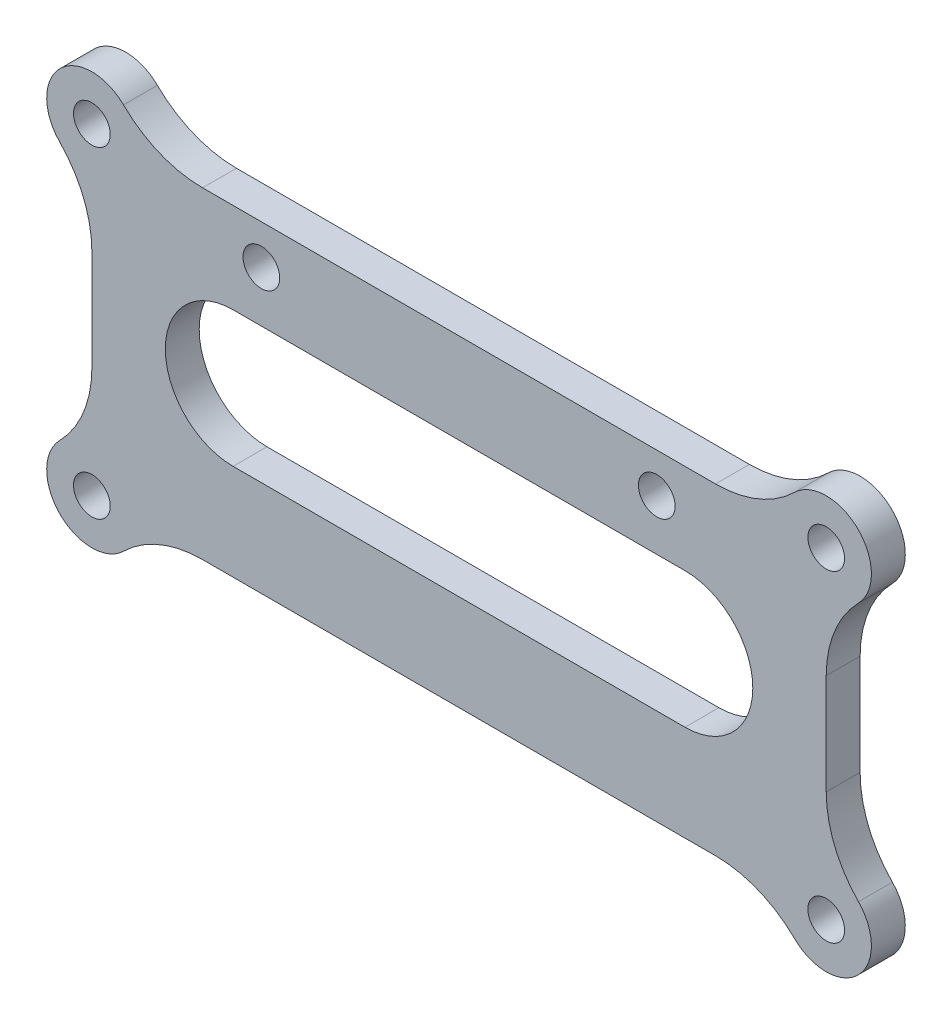
SolidWorks part; units mm, degrees
material "ABS"
ref_plane "Спереди" through (0, 0, 0) normal (0, 0, 1) x (1, 0, 0)
ref_plane "Сверху" through (0, 0, 0) normal (0, 1, 0) x (1, 0, 0)
ref_plane "Справа" through (0, 0, 0) normal (1, 0, 0) x (0, 0, -1)
sketch "Эскиз1" plane through (0, 0, 0) normal (0, 0, 1) x (1, 0, 0)
  line L0 (-32.5, 0) -> (32.5, 0)
  line L3 (-32.5, 28.5) -> (32.5, 28.5)
  line L4 (32.5, 0) -> (32.5, 28.5)
  line L6 (-32.5, 28.5) -> (0, 0) construction
  line L7 (-32.5, 0) -> (-32.5, 28.5)
  line L8 (0, 0) -> (32.5, 28.5) construction
  circle A0 centre (-32.5, 28.5) radius 1.625
  arc A1 (-28.5, 28.5) -> (-32.5, 24.5) centre (-32.5, 28.5) ccw
  circle A2 centre (32.5, 28.5) radius 1.625
  arc A3 (32.5, 24.5) -> (28.5, 28.5) centre (32.5, 28.5) ccw
  arc A8 (-30.2165, -39.7842) -> (-30.0697, -39.6771) centre (-32.5, -36.5) ccw [skipped]
  arc A9 (-30.8963, -36.7625) -> (-30.8944, -36.7501) centre (-32.5, -36.5) ccw [skipped]
  arc A10 (34.8906, -39.707) -> (34.7835, -39.7842) centre (32.5, -36.5) ccw [skipped]
  arc A11 (34.1056, -36.7501) -> (34.1094, -36.7244) centre (32.5, -36.5) ccw [skipped]
  circle A12 centre (-32.5, 0) radius 1.625
  arc A13 (-32.5, 4) -> (-28.5, 0) centre (-32.5, 0) ccw
  arc A14 (28.5, 0) -> (32.5, 4) centre (32.5, 0) ccw
  circle A15 centre (32.5, 0) radius 1.625
  point P0 (0, 0)
  point P20 (0, -4)
  dimension "D2" = 3.25
  dimension "D3" = 8
  dimension "D8" = 3.25
  dimension "D9" = 8
  dimension "D10" = 3.25
  dimension "D11" = 8
  dimension "D1" = 28.5
  dimension "D5" = 65
  dimension "D6" = 32.5
  dimension "D7" = 90
  dimension "D4" = 4
extrude "Бобышка-Вытянуть1" add sketch "Эскиз1" along normal blind 3
fillet "Скругление1" radius 10 8 edges at (-28.5, 28.5, 1.5) (28.5, 28.5, 1.5) (32.5, 24.5, 1.5) (-32.5, 24.5, 1.5) (32.5, 4, 1.5) (28.5, 0, 1.5) (-28.5, 0, 1.5) (-32.5, 4, 1.5)
sketch "Эскиз3" plane through (0, 0, 0) normal (0, 0, -1) x (-1, 0, 0)
  line L0 (0, 28.5) -> (0, -32.5) construction
  line L1 (22.702, 28.5) -> (-22.702, 28.5) construction
  line L3 (-31.8936, 25) -> (26.7306, 25) construction
  circle A0 centre (-17.5, 25) radius 1.625
  circle A1 centre (17.5, 25) radius 1.625
  dimension "D1" = 3.25
  dimension "D2" = 17.5
  dimension "D3" = 25
extrude "Вырез-Вытянуть1" cut sketch "Эскиз3" against normal blind 10
sketch "Эскиз4" plane through (0, 0, 3) normal (0, 0, 1) x (1, 0, 0)
  line L0 (-32.5, 10) -> (32.5, 10) construction
  line L1 (-32.5, 9.798) -> (-32.5, 18.702) construction
  line L2 (32.5, 9.798) -> (32.5, 18.702) construction
  line L3 (0, 28.5) -> (0, 0) construction
  line L4 (-22.702, 28.5) -> (22.702, 28.5) construction
  line L5 (-16.3, 18.1339) -> (-16.3, 8.5971) construction
  circle A0 centre (-26.6, 10) radius 1.625
  circle A1 centre (-6, 10) radius 1.625
  circle A2 centre (6, 10) radius 1.625
  circle A3 centre (26.6, 10) radius 1.625
  dimension "D4" = 3.25
  dimension "D1" = 20.6
  dimension "D2" = 6
  dimension "D3" = 10
extrude "Вырез-Вытянуть2" [suppressed] cut sketch "Эскиз4" against normal blind 10
sketch "Эскиз6" plane through (0, 0, 3) normal (0, 0, 1) x (1, 0, 0)
  line L0 (-21.15, 14.05) -> (-8.65, 14.05)
  line L1 (-8.45, 13.85) -> (-8.45, 6.15)
  line L2 (-21.15, 5.95) -> (-8.65, 5.95)
  line L3 (-24.15, 11.05) -> (-24.15, 8.95)
  line L4 (-24.15, 10) -> (-8.45, 10) construction
  line L6 (0, 28.5) -> (0, 0) construction
  line L11 (-22.702, 28.5) -> (22.702, 28.5) construction
  line L12 (-21.15, 14.3) -> (-8.65, 14.3)
  line L13 (-8.2, 13.85) -> (-8.2, 6.15)
  line L14 (-21.15, 5.7) -> (-8.65, 5.7)
  line L15 (-24.4, 11.05) -> (-24.4, 8.95)
  arc A1 (-8.45, 13.85) -> (-8.65, 14.05) centre (-8.65, 13.85) ccw
  arc A2 (-8.65, 5.95) -> (-8.45, 6.15) centre (-8.65, 6.15) ccw
  arc A3 (-21.15, 14.05) -> (-24.15, 11.05) centre (-21.15, 11.05) ccw
  arc A4 (-21.15, 5.95) -> (-24.15, 8.95) centre (-21.15, 8.95) cw
  arc A9 (-8.2, 13.85) -> (-8.65, 14.3) centre (-8.65, 13.85) ccw
  arc A10 (-8.65, 5.7) -> (-8.2, 6.15) centre (-8.65, 6.15) ccw
  arc A11 (-21.15, 5.7) -> (-24.4, 8.95) centre (-21.15, 8.95) cw
  arc A12 (-21.15, 14.3) -> (-24.4, 11.05) centre (-21.15, 11.05) ccw
  dimension "D1" = 0.25
extrude "Вырез-Вытянуть3" [suppressed] cut sketch "Эскиз6" against normal blind 10
mirror "Зеркальное отражение1" [suppressed] about plane through (0, 0, 0) normal (1, 0, 0)
sketch "Эскиз7" plane through (0, 0, 3) normal (0, 0, 1) x (1, 0, 0)
  line L0 (0, 28.5) -> (0, 0) construction
  line L1 (-22.702, 28.5) -> (22.702, 28.5) construction
  line L2 (-20, 14.5) -> (20, 14.5) construction
  line L3 (-20, 20.5) -> (20, 20.5)
  line L4 (-20, 8.5) -> (20, 8.5)
  arc A0 (-20, 20.5) -> (-20, 8.5) centre (-20, 14.5) ccw
  arc A1 (20, 8.5) -> (20, 20.5) centre (20, 14.5) ccw
  point P7 (0, 14.5)
  dimension "D1" = 40
  dimension "D2" = 12
  dimension "D3" = 8
extrude "Вырез-Вытянуть4" cut sketch "Эскиз7" against normal blind 10
